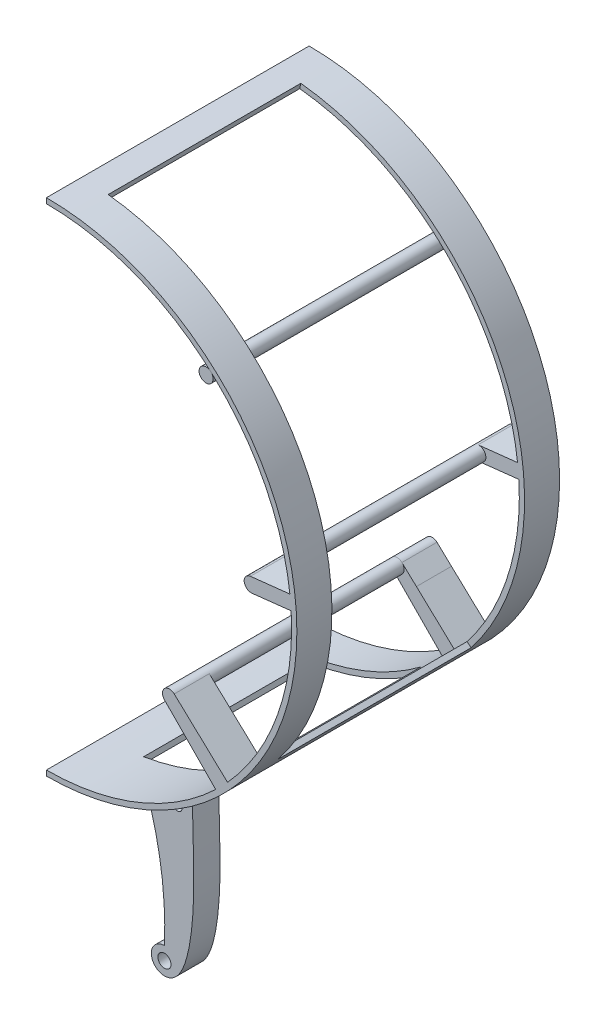
SolidWorks part; units mm, degrees
material "1023 Carbon Steel Sheet (SS)"
ref_plane "Front Plane" through (0, 0, 0) normal (0, 0, 1) x (1, 0, 0)
ref_plane "Top Plane" through (0, 0, 0) normal (0, 1, 0) x (1, 0, 0)
ref_plane "Right Plane" through (0, 0, 0) normal (1, 0, 0) x (0, 0, -1)
ref_plane "Plane2" through (0, 0, 50.1) normal (0, 0, 1) x (1, 0, 0)
sketch "Sketch1" plane through (0, 0, 0) normal (0, 0, 1) x (1, 0, 0)
  line L0 (0, -143) -> (0, -140)
  line L1 (0, 143) -> (0, 140)
  arc A0 (0, -140) -> (0, 140) centre (0, 0) ccw
  arc A1 (0, -143) -> (0, 143) centre (0, 0) ccw
  dimension "D1" = 280
  dimension "D2" = 3
extrude "Boss-Extrude1" add sketch "Sketch1" along normal mid plane 150
ref_plane "Plane1" through (0, 0, 37.5) normal (0, 0, 1) x (1, 0, 0)
sketch "Sketch2" plane through (0, 0, 50.1) normal (0, 0, 1) x (1, 0, 0)
  line L1 (39.3632, -137.4756) -> (65.554, -126.3417)
  circle A0 centre (50, -218.0191) radius 3.75
  arc A1 (50, -210.5177) -> (50, -225.5205) centre (50, -218.0191) ccw
  arc A2 (0, -143) -> (0, 143) centre (0, 0) ccw construction
  circle A8 centre (57.4915, -137.7366) radius 2.5
  spline S0 degree 2 poles (50, -210.5177) (51.5798, -173.0413) (39.3632, -137.4756) knots 0 0 0 1 1 1
  spline S1 degree 3 poles (50, -225.5205) (63.888, -225.5567) (66.6724, -185.5186) (66.8285, -159.2266) (65.8373, -126.4348) (65.554, -126.3417) knots 0 0 0 0 0.384311 0.484311 1 1 1 1
  dimension "D1" = 7.5
extrude "Boss-Extrude2" add sketch "Sketch2" along normal mid plane 15
sketch "Sketch3" plane through (0, 0, 0) normal (0, 0, 1) x (1, 0, 0)
  line L0 (0, 0) -> (0, -341.9209) construction
sketch "Sketch4" plane through (0, 0, 0) normal (0, 0, 1) x (1, 0, 0)
  circle A0 centre (0, 26) radius 114 construction
  arc A1 (0, -140) -> (0, 140) centre (0, 0) ccw construction
  circle A2 centre (91.1621, 100.9231) radius 4
  circle A3 centre (116.9178, 10.0554) radius 4
  circle A4 centre (70.2497, -68.8103) radius 4
  dimension "D1" = 228
  dimension "D2" = 8
  dimension "D3" = 8
  dimension "D4" = 8
extrude "Boss-Extrude3" add sketch "Sketch4" along normal mid plane 150 separate body
sketch "Sketch5" plane through (0, 0, 75) normal (0, 0, 1) x (1, 0, 0)
  line L0 (67.4018, -71.6191) -> (98.3819, -103.03)
  line L1 (72.9832, -65.89) -> (105.049, -95.9057)
  line L2 (98.3819, -103.03) -> (105.049, -95.9057)
  line L3 (116.4789, 14.0312) -> (141.1385, 16.7534)
  line L4 (117.3641, 6.0804) -> (142.2496, 8.8748)
  line L5 (141.1385, 16.7534) -> (142.2496, 8.8748)
  circle A0 centre (70.2497, -68.8103) radius 4 construction
  arc A2 (72.9832, -65.89) -> (67.4018, -71.6191) centre (70.2497, -68.8103) ccw
  circle A3 centre (116.9178, 10.0554) radius 4 construction
  arc A5 (116.4789, 14.0312) -> (117.3641, 6.0804) centre (116.9178, 10.0554) ccw
extrude "Boss-Extrude4" add sketch "Sketch5" against normal blind 20 from surface at 0 starting at face at (70.75, 0, 75)
sketch "Sketch10" plane through (0, 0, -75) normal (0, 0, -1) x (-1, 0, 0)
  line L0 (-81.264, -73.6414) -> (-72.9835, -65.8899)
  line L1 (-72.9832, -65.89) -> (-103.411, -94.3725) construction
  line L2 (-81.264, -73.6414) -> (-103.9095, -94.8391)
  line L3 (-71.7154, -75.9927) -> (-67.4017, -71.6194)
  line L4 (-96.6559, -101.28) -> (-67.4018, -71.6191) construction
  line L5 (-71.7154, -75.9927) -> (-97.325, -101.956)
  line L6 (-97.325, -101.956) -> (-103.9095, -94.8391)
  line L7 (-129.7828, 15.4999) -> (-116.4789, 14.0312)
  line L8 (-116.4789, 14.0312) -> (-139.0219, 16.5198) construction
  line L10 (-139.7361, 8.5925) -> (-117.3641, 6.0804) construction
  line L11 (-131.966, 7.72) -> (-117.3641, 6.0804)
  line L12 (-129.7828, 15.4999) -> (-139.7427, 16.5993)
  line L14 (-131.966, 7.72) -> (-140.6174, 8.675)
  line L15 (-140.6174, 8.675) -> (-139.7427, 16.5993)
  arc A0 (-67.4017, -71.6194) -> (-72.9835, -65.8899) centre (-70.2497, -68.8103) ccw
  arc A1 (-117.3641, 6.0804) -> (-116.4789, 14.0312) centre (-116.9178, 10.0554) ccw
extrude "Boss-Extrude5" add sketch "Sketch10" against normal blind 20
sketch "Sketch14" plane through (0, 0, 0) normal (0, 0, 1) x (1, 0, 0)
  line L5 (110.0513, -86.3712) -> (112.492, -88.2867)
  line L8 (14.626, 139.1307) -> (15.2613, 142.1833)
  arc A0 (110.0513, -86.3712) -> (139.8909, 1.3435) centre (0, 0) ccw
  arc A1 (112.492, -88.2867) -> (142.9907, 1.6312) centre (0, 0) ccw
  arc A2 (0, -143) -> (0, 143) centre (0, 0) ccw construction
  arc A3 (139.8909, 1.3435) -> (101.5408, 96.2328) centre (0, 0) ccw
  arc A4 (142.9907, 1.6312) -> (103.4681, 98.7084) centre (0, 0) ccw
  arc A5 (101.5408, 96.2328) -> (14.626, 139.1307) centre (0, 0) ccw
  arc A6 (103.4681, 98.7084) -> (15.2613, 142.1833) centre (0, 0) ccw
extrude "Cut-Extrude1" cut sketch "Sketch14" against normal up to surface and the other way up to surface up to face at (66.2497, -68.8103, -55) other way up to face at (85.8584, -84.0167, 55)
sketch "Sketch15" plane through (0, 0, 0) normal (0, 0, 1) x (1, 0, 0)
  line L0 (86.5353, -110.0529) -> (88.3896, -112.4112)
  line L1 (20.5584, -138.4823) -> (20.9989, -141.4498)
  arc A0 (20.5584, -138.4823) -> (86.5353, -110.0529) centre (0, 0) ccw
  arc A1 (20.9989, -141.4498) -> (88.3896, -112.4112) centre (0, 0) ccw
sketch "Sketch16" plane through (0, 0, 0) normal (0, 0, 1) x (1, 0, 0)
  line L2 (83.8476, -112.1142) -> (85.6443, -114.5166)
  line L3 (23.1038, -138.0805) -> (23.5989, -141.0393)
  line L4 (0, 0) -> (83.8476, -112.1142) construction
  arc A0 (0, -143) -> (0, 143) centre (0, 0) ccw construction
  arc A4 (23.5989, -141.0393) -> (85.6443, -114.5166) centre (0, 0) ccw
  arc A5 (23.1038, -138.0805) -> (83.8476, -112.1142) centre (0, 0) ccw
  arc A6 (0, -140) -> (96.6559, -101.28) centre (0, 0) ccw construction
extrude "Cut-Extrude3" cut sketch "Sketch16" along normal up to surface (97.6 mm away) from surface at 42.6
